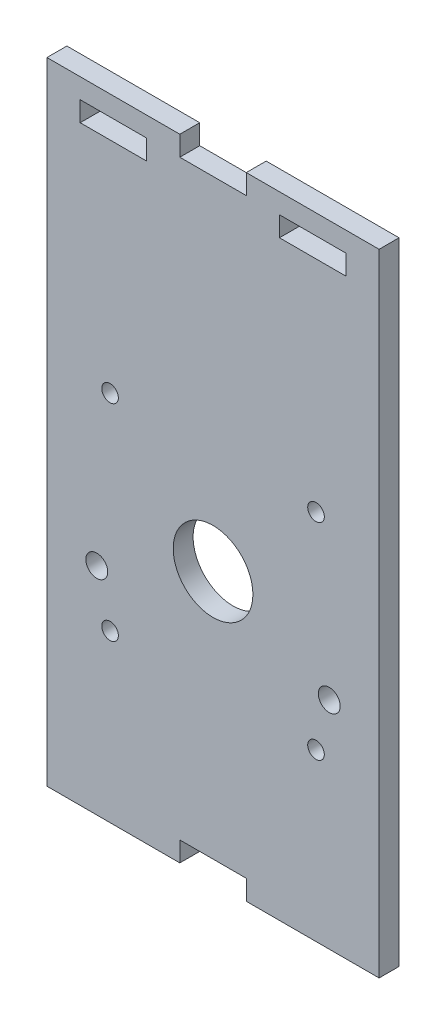
SolidWorks part; units mm, degrees
ref_plane "Front Plane" through (0, 0, 0) normal (0, 0, 1) x (1, 0, 0)
ref_plane "Top Plane" through (0, 0, 0) normal (0, 1, 0) x (1, 0, 0)
ref_plane "Right Plane" through (0, 0, 0) normal (1, 0, 0) x (0, 0, -1)
sketch "Sketch1" plane through (0, 0, 0) normal (0, 0, 1) x (1, 0, 0)
  line L0 (25, 5) -> (25, -5.5)
  line L1 (-25, -40.5) -> (-5, -40.5)
  line L2 (-25, -40.5) -> (-25, -5.5)
  line L4 (25, -40.5) -> (25, -5.5)
  line L5 (-25, -40.5) -> (25, 24.5) construction
  line L6 (-25, 24.5) -> (25, -40.5) construction
  line L13 (25, 5) -> (25, 24.5)
  line L18 (-25, 4.5) -> (-25, 24.5)
  line L24 (0, 0) -> (27.5, 0) construction
  line L25 (5, -40.5) -> (5, -37.5)
  line L26 (-5, -37.5) -> (5, -37.5)
  line L27 (-5, -40.5) -> (-5, -37.5)
  line L28 (5, -40.5) -> (25, -40.5)
  line L29 (-25, 24.5) -> (-25, 54.5)
  line L30 (-25, 54.5) -> (-5, 54.5)
  line L31 (25, 54.5) -> (25, 24.5)
  line L32 (5, 54.5) -> (25, 54.5)
  line L34 (-5, 54.5) -> (-5, 51.5)
  line L35 (-5, 51.5) -> (5, 51.5)
  line L36 (5, 54.5) -> (5, 51.5)
  line L37 (-25, 4.5) -> (-25, -5.5)
  line L38 (0, 44.5) -> (0, 25) construction
  line L39 (16, 44.5) -> (-16, 44.5) construction
  line L40 (20, 48.5) -> (10, 51.5) construction
  line L41 (-20, 51.5) -> (-10, 51.5)
  line L42 (-20, 51.5) -> (-20, 48.5)
  line L43 (-20, 48.5) -> (-10, 48.5)
  line L44 (-10, 51.5) -> (-10, 48.5)
  line L45 (-20, 51.5) -> (-10, 48.5) construction
  line L46 (-20, 48.5) -> (-10, 51.5) construction
  line L47 (20, 51.5) -> (10, 48.5) construction
  line L48 (10, 51.5) -> (10, 48.5)
  line L49 (20, 48.5) -> (10, 48.5)
  line L50 (20, 51.5) -> (20, 48.5)
  line L51 (20, 51.5) -> (10, 51.5)
  circle A0 centre (0, 0) radius 6
  circle A4 centre (-15.5, 15.5) radius 1.25
  circle A6 centre (15.5, 15.5) radius 1.25
  circle A8 centre (15.5, -15.5) radius 1.25
  circle A10 centre (-15.5, -15.5) radius 1.25
  circle A16 centre (-17.5, -8) radius 1.65
  circle A17 centre (17.5, -8) radius 1.65
  point P12 (25, 0)
  point P13 (0, 0)
  point P16 (0, 55)
  point P19 (-20.9567, 31.7184)
  point P28 (0, 0)
  point P32 (0, 25)
  point P37 (-15, 50)
  point P42 (0, -25)
  point P54 (15, 50)
  dimension "D9" = 2.5
  dimension "D10" = 12
  dimension "D11" = 3.3
  dimension "D15" = 20
  dimension "D2" = 35
  dimension "D3" = 20
  dimension "D4" = 10
  dimension "D5" = 20
  dimension "D6" = 3
  dimension "D7" = 50
  dimension "D8" = 30
  dimension "D12" = 10
  dimension "D13" = 35
  dimension "D14" = 10
  dimension "D16" = 3
  dimension "D17" = 10
  dimension "D18" = 0
  dimension "D19" = 5
extrude "Boss-Extrude2" add sketch "Sketch1" along normal blind 3
equation "\"D\"=3"
equation "\"D1@Boss-Extrude2\"=\"D\""
